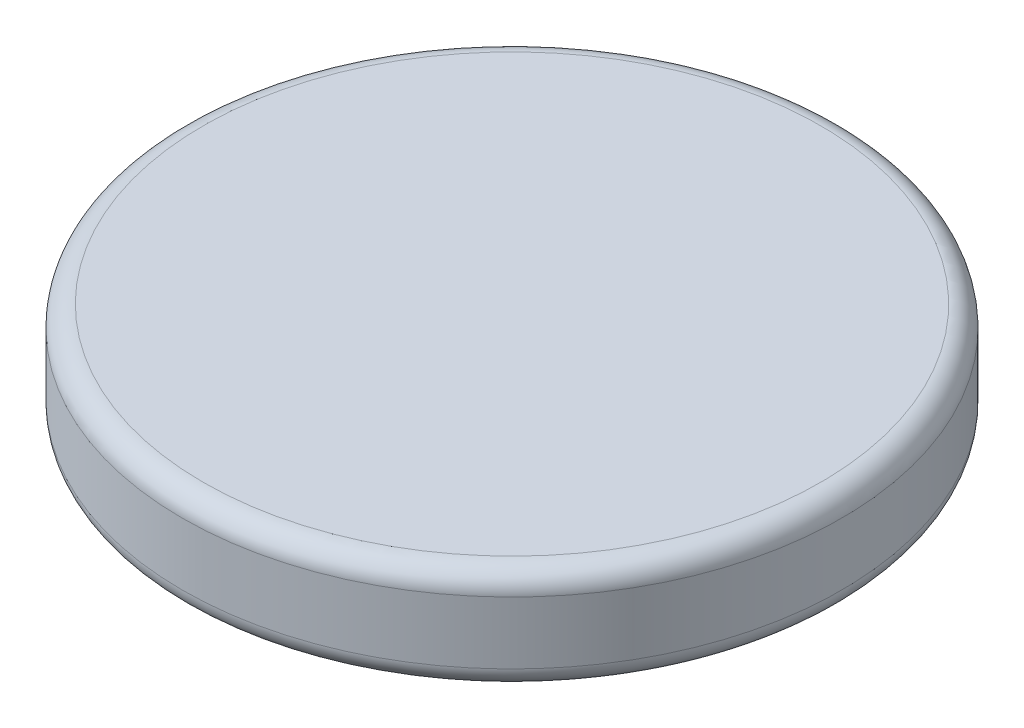
SolidWorks part; units mm, degrees
ref_plane "Front Plane" through (0, 0, 0) normal (0, 0, 1) x (1, 0, 0)
ref_plane "Top Plane" through (0, 0, 0) normal (0, 1, 0) x (1, 0, 0)
ref_plane "Right Plane" through (0, 0, 0) normal (1, 0, 0) x (0, 0, -1)
sketch "Sketch3" plane through (0, 0, 0) normal (0, 1, 0) x (1, 0, 0)
  circle A0 centre (0, 0) radius 317.5
  dimension "D1" = 635
extrude "Boss-Extrude2" add sketch "Sketch3" along normal blind 100
fillet "Fillet5" radius 20 2 edges at (0, 0, 317.5) (0, 100, 317.5)
sketch "Sketch4" plane through (0, 0, 0) normal (0, 1, 0) x (1, 0, 0)
  circle A0 centre (0, 0) radius 50.8
  circle A1 centre (0, 0) radius 63.5
  dimension "D1" = 101.6
  dimension "D2" = 127
extrude "Boss-Extrude3" add sketch "Sketch4" against normal blind 10
